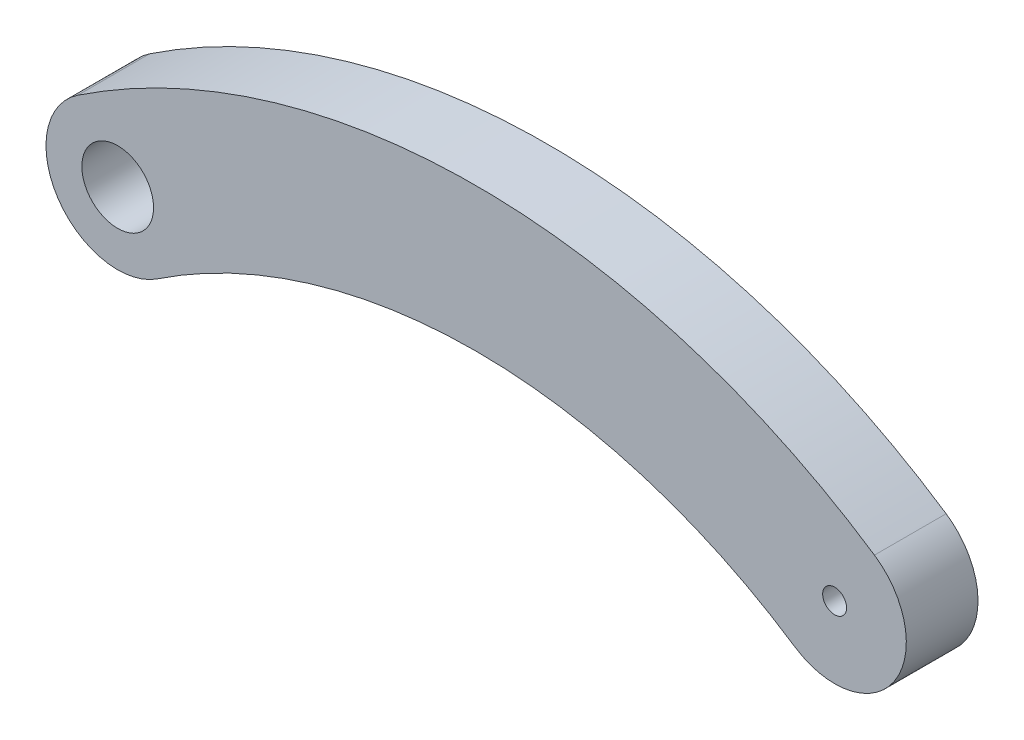
SolidWorks part; units mm, degrees
ref_plane "前视基准面" through (0, 0, 0) normal (0, 0, 1) x (1, 0, 0)
ref_plane "上视基准面" through (0, 0, 0) normal (0, 1, 0) x (1, 0, 0)
ref_plane "右视基准面" through (0, 0, 0) normal (1, 0, 0) x (0, 0, -1)
other "Configuration Table"
sketch "草图1" plane through (0, 0, 0) normal (0, 0, 1) x (1, 0, 0)
  line L0 (0, 0) -> (30, 0) construction
  circle A2 centre (0, 0) radius 1.5
  circle A3 centre (30, 0) radius 1.5
  arc A4 (31.6667, 2.4944) -> (-1.6667, 2.4944) centre (15, -22.4499) ccw
  arc A5 (28.3333, -2.4944) -> (31.6667, 2.4944) centre (30, 0) ccw
  arc A6 (-1.6667, 2.4944) -> (1.6667, -2.4944) centre (0, 0) ccw
  arc A7 (28.3333, -2.4944) -> (1.6667, -2.4944) centre (15, -22.4499) ccw
  point P3 (15, 0)
  dimension "D2" = 6
  dimension "D3" = 3
  dimension "D4" = 3
  dimension "D5" = 6
  dimension "D6" = 60
  dimension "D1" = 30
extrude "凸台-拉伸1" add sketch "草图1" along normal blind 3
sketch "草图2" plane through (0, 0, 3) normal (0, 0, 1) x (1, 0, 0)
  circle A0 centre (30, 0) radius 0.5
  circle A1 centre (30, 0) radius 1.5 construction
  circle A2 centre (30, 0) radius 1.5
  dimension "D1" = 1
extrude "凸台-拉伸2" add sketch "草图2" against normal through all
